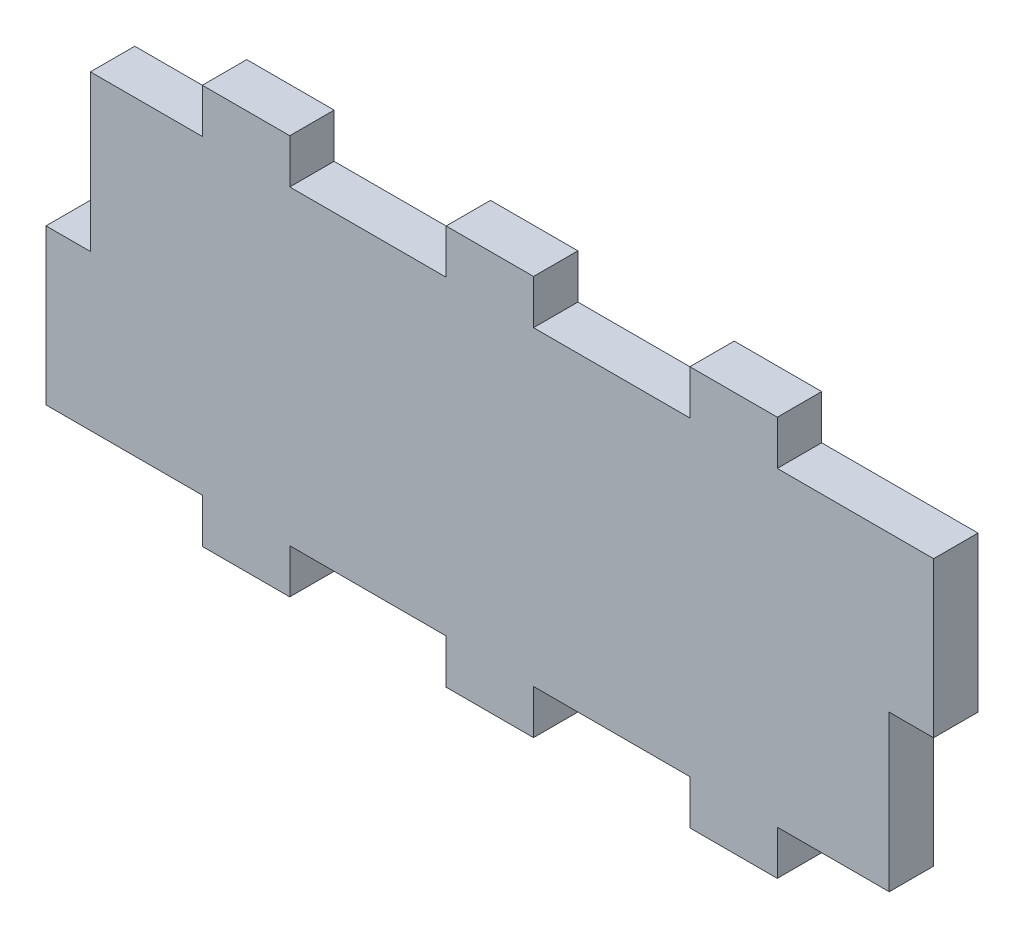
SolidWorks part; units mm, degrees
ref_plane "Front Plane" through (0, 0, 0) normal (0, 0, 1) x (1, 0, 0)
ref_plane "Top Plane" through (0, 0, 0) normal (0, 1, 0) x (1, 0, 0)
ref_plane "Right Plane" through (0, 0, 0) normal (1, 0, 0) x (0, 0, -1)
sketch "Sketch2" plane through (0, 0, 0) normal (0, 0, 1) x (1, 0, 0)
  line L0 (-32.3875, 22.5) -> (-32.3875, 17.5)
  line L1 (-45, -17.5) -> (45, -17.5)
  line L2 (-45, -17.5) -> (-45, 17.5)
  line L3 (-45, 17.5) -> (45, 17.5)
  line L4 (45, -17.5) -> (45, 17.5)
  line L5 (-45, -17.5) -> (45, 17.5) construction
  line L6 (-45, 17.5) -> (45, -17.5) construction
  line L7 (-45, -17.5) -> (-50, -17.5)
  line L8 (-45, -17.5) -> (-45, -0.025)
  line L9 (-45, -0.025) -> (-50, -0.025)
  line L10 (-50, -17.5) -> (-50, -0.025)
  line L11 (-32.3875, -17.5) -> (-22.5375, -17.5)
  line L12 (-32.3875, -17.5) -> (-32.3875, -22.5)
  line L13 (-32.3875, -22.5) -> (-22.5375, -22.5)
  line L14 (-22.5375, -17.5) -> (-22.5375, -22.5)
  line L15 (-4.925, -17.5) -> (4.925, -17.5)
  line L16 (-4.925, -17.5) -> (-4.925, -22.5)
  line L17 (-4.925, -22.5) -> (4.925, -22.5)
  line L18 (4.925, -17.5) -> (4.925, -22.5)
  line L19 (22.5375, -17.5) -> (32.3875, -17.5)
  line L20 (22.5375, -17.5) -> (22.5375, -22.5)
  line L21 (22.5375, -22.5) -> (32.3875, -22.5)
  line L22 (32.3875, -17.5) -> (32.3875, -22.5)
  line L23 (45, 17.5) -> (50, 17.5)
  line L24 (45, 17.5) -> (45, 0.025)
  line L25 (45, 0.025) -> (50, 0.025)
  line L26 (50, 17.5) -> (50, 0.025)
  line L27 (-32.3875, 22.5) -> (-22.5375, 22.5)
  line L28 (-22.5375, 22.5) -> (-22.5375, 17.5)
  line L29 (-32.3875, 17.5) -> (-22.5375, 17.5)
  line L30 (-4.925, 22.5) -> (-4.925, 17.5)
  line L31 (-4.925, 22.5) -> (4.925, 22.5)
  line L32 (4.925, 22.5) -> (4.925, 17.5)
  line L33 (-4.925, 17.5) -> (4.925, 17.5)
  line L34 (22.5375, 22.5) -> (22.5375, 17.5)
  line L35 (22.5375, 22.5) -> (32.3875, 22.5)
  line L36 (32.3875, 22.5) -> (32.3875, 17.5)
  line L37 (22.5375, 17.5) -> (32.3875, 17.5)
  line L38 (22.5375, -20) -> (4.925, -20) construction
  line L39 (-4.925, -20) -> (-22.5375, -20) construction
  line L42 (32.3875, -20) -> (50, -20) construction
  line L43 (50, -20) -> (50, 0.025) construction
  line L44 (-32.3875, -20) -> (-50, -20) construction
  line L45 (-50, -20) -> (-50, -17.5) construction
  point P0 (0, 0)
  dimension "D1" = 35
  dimension "D2" = 90
  dimension "D3" = 17.475
  dimension "D4" = 5
  dimension "D5" = 5
  dimension "D6" = 5
  dimension "D7" = 5
  dimension "D8" = 9.85
  dimension "D9" = 9.85
  dimension "D10" = 9.85
  dimension "D13" = 5
  dimension "D14" = 17.475
  dimension "D16" = 2
extrude "Boss-Extrude1" add sketch "Sketch2" along normal blind 5 contours L1 L4 L3 L2 | L10 L7 L2 L9 | L28 L27 L0 L3 | L32 L31 L30 L3 | L36 L35 L34 L3 | L26 L23 L4 L25 | L22 L1 L20 L21 | L18 L1 L16 L17 | L14 L1 L12 L13
